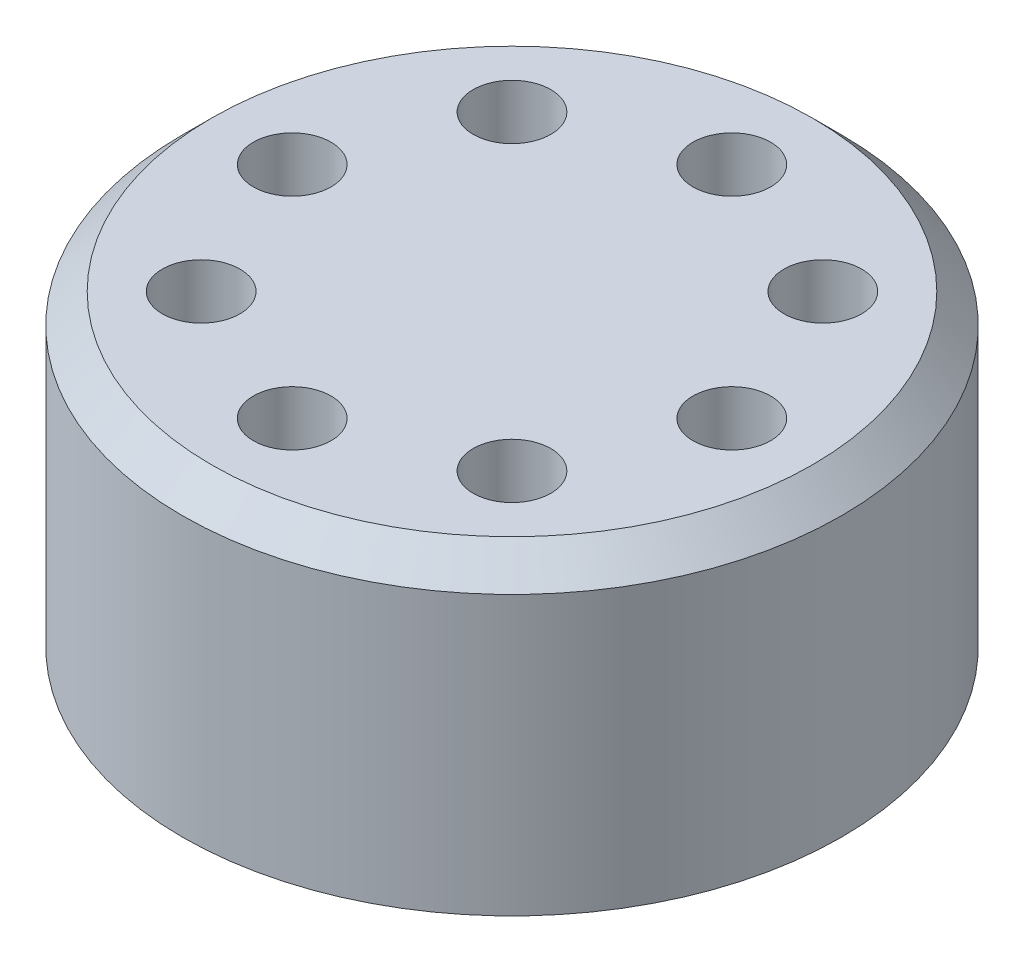
SolidWorks part; units mm, degrees
ref_plane "Front Plane" through (0, 0, 0) normal (0, 0, 1) x (1, 0, 0)
ref_plane "Top Plane" through (0, 0, 0) normal (0, 1, 0) x (1, 0, 0)
ref_plane "Right Plane" through (0, 0, 0) normal (1, 0, 0) x (0, 0, -1)
sketch "Sketch1" plane through (0, 0, 0) normal (0, 1, 0) x (1, 0, 0)
  circle A0 centre (0, 0) radius 22.5
  dimension "D1" = 45
extrude "Boss-Extrude1" add sketch "Sketch1" along normal blind 21
chamfer "Chamfer1" distance 2 angle 45 1 edges at (0, 21, 22.5)
hole_wizard "M5 Clearance Hole1" positions "Sketch2" profile "Sketch3" hole size "M5" standard "ANSI Metric" end condition through all
sketch "Sketch2" plane through (0, 21, 0) normal (0, 1, 0) x (1, 0, 0)
  line L0 (0, 0) -> (15, 0) construction
  line L2 (0, 0) -> (10.6066, 10.6066) construction
  circle A0 centre (0, 0) radius 15 construction
  point P5 (0, 15)
  point P7 (15, 0)
  point P9 (0, -15)
  point P11 (-15, 0)
  point P20 (10.6066, 10.6066)
  point P30 (10.6066, -10.6066)
  point P31 (-10.6066, -10.6066)
  point P32 (-10.6066, 10.6066)
  dimension "D1" = 30
  dimension "D2" = 45
  dimension "D3" = 4
sketch "Sketch3" plane through (-10.6066, 21, -10.6066) normal (1, 0, 0) x (0, 0, 1)
  line L0 (0, 0) -> (0, 21)
  line L1 (0, 21) -> (2.65, 21)
  line L2 (2.65, 21) -> (2.65, 0)
  line L5 (2.65, 0) -> (0, 0)
  line L11 (0, -6.35) -> (0, 107.95) construction
  dimension "Thru Hole Dia." = 5.3
  dimension "Thru Hole Depth" = 21
